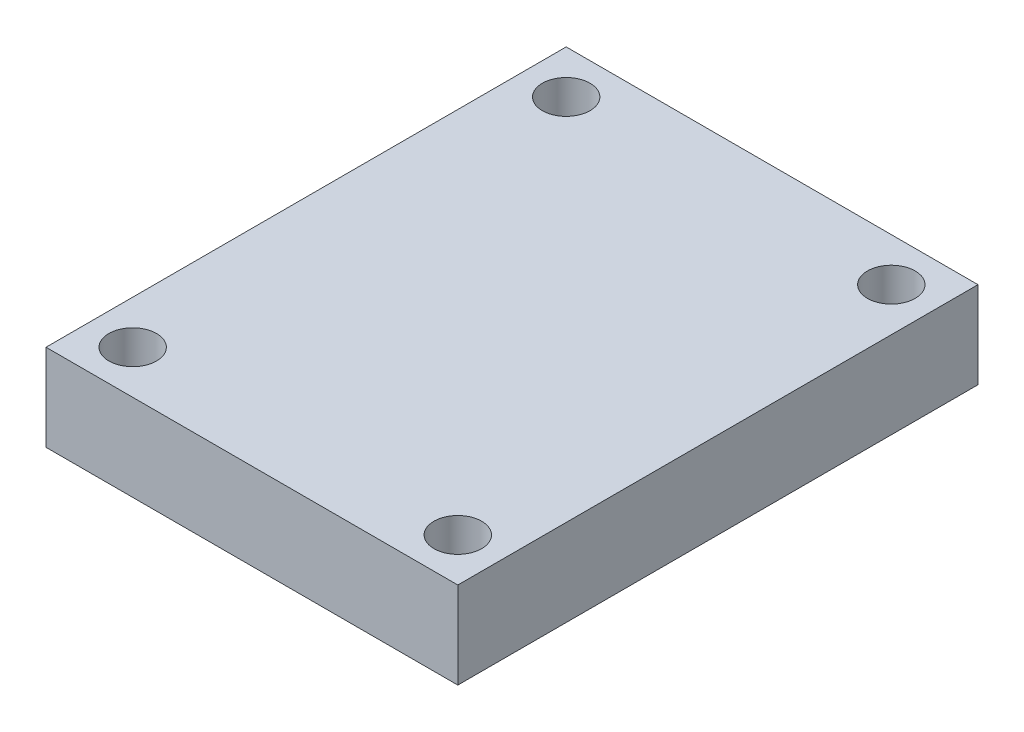
SolidWorks part; units mm, degrees
ref_plane "Plan de face" through (0, 0, 0) normal (0, 0, 1) x (1, 0, 0)
ref_plane "Plan de dessus" through (0, 0, 0) normal (0, 1, 0) x (1, 0, 0)
ref_plane "Plan de droite" through (0, 0, 0) normal (1, 0, 0) x (0, 0, -1)
sketch "Esquisse1" plane through (0, 0, 0) normal (0, 1, 0) x (1, 0, 0)
  line L0 (0, 0) -> (0, 48)
  line L1 (0, 48) -> (-8, 48)
  line L2 (-8, 48) -> (-8, 0) construction
  line L3 (-8, 0) -> (0, 0)
  line L4 (-8, 0) -> (-30, 0)
  line L5 (-8, 48) -> (-38, 48)
  line L7 (-38, 0) -> (-30, 0)
  line L8 (-30, 0) -> (-38, 8) construction
  line L9 (-38, 0) -> (-38, 48)
  line L10 (-30, 8) -> (-30, 40) construction
  line L11 (-30, 40) -> (-30, 48) construction
  line L12 (-30, 48) -> (-38, 48) construction
  line L13 (-38, 40) -> (-30, 40) construction
  line L14 (-30, 40) -> (-38, 48) construction
  line L15 (-38, 0) -> (-38, 8) construction
  line L16 (-38, 8) -> (-30, 8) construction
  line L17 (-30, 8) -> (-38, 0) construction
  line L18 (-38, 40) -> (-30, 48) construction
  line L20 (-8, 48) -> (-8, 40) construction
  line L21 (-8, 40) -> (0, 40) construction
  line L22 (0, 40) -> (-8, 48) construction
  line L23 (-8, 40) -> (0, 48) construction
  line L24 (-8, 0) -> (-8, 8) construction
  line L25 (-8, 8) -> (0, 0) construction
  line L26 (0, 8) -> (-8, 0) construction
  circle A0 centre (-4, 4) radius 2.2
  circle A1 centre (-4, 44) radius 2.2
  circle A2 centre (-34, 4) radius 2.2
  circle A4 centre (-34, 44) radius 2.2
extrude "Boss.-Extru.1" add sketch "Esquisse1" along normal blind 8
